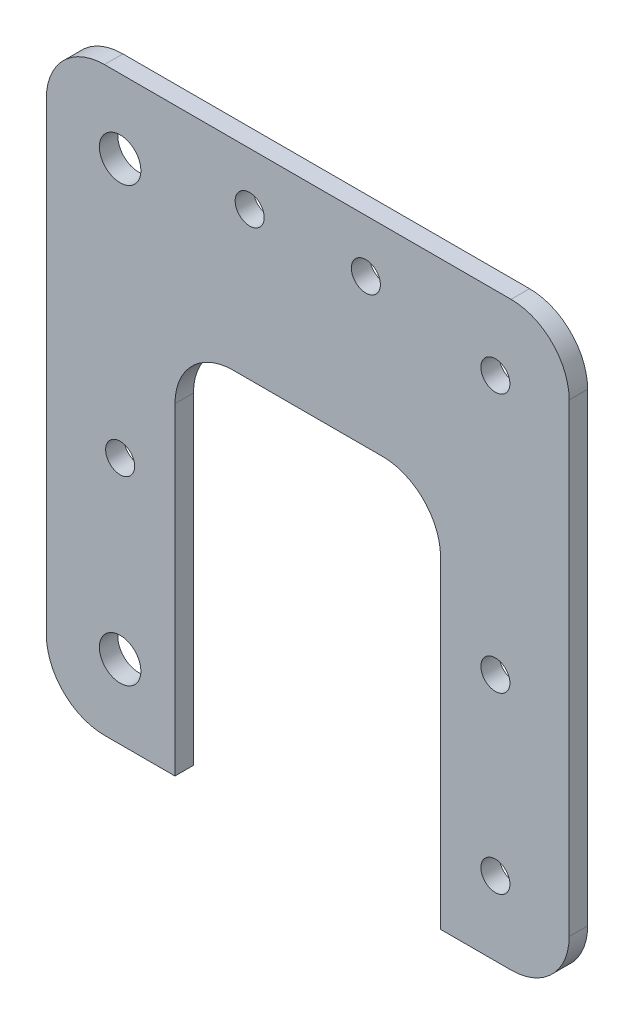
SolidWorks part; units mm, degrees
ref_plane "Front Plane" through (0, 0, 0) normal (0, 0, 1) x (1, 0, 0)
ref_plane "Top Plane" through (0, 0, 0) normal (0, 1, 0) x (1, 0, 0)
ref_plane "Right Plane" through (0, 0, 0) normal (1, 0, 0) x (0, 0, -1)
sketch "Sketch1" plane through (0, 0, 0) normal (0, 0, 1) x (1, 0, 0)
  line L1 (-45, -55) -> (45, -55)
  line L2 (-45, -55) -> (-45, 45)
  line L3 (-45, 45) -> (45, 45)
  line L4 (45, -55) -> (45, 45)
  line L8 (-32.3, 32.3) -> (-32.3, -42.3) construction
  line L9 (-32.3, -42.3) -> (32.3, -42.3) construction
  line L10 (32.3, -42.3) -> (32.3, 32.3) construction
  line L11 (32.3, 32.3) -> (-32.3, 32.3) construction
  line L12 (32.3, -12.3) -> (-32.3, -12.3) construction
  circle A4 centre (32.3, -12.3) radius 2.5
  circle A5 centre (32.3, -42.3) radius 2.5
  circle A6 centre (-32.3, -42.3) radius 3.57
  circle A7 centre (-32.3, -12.3) radius 2.5
  circle A9 centre (-32.3, 32.3) radius 3.57
  circle A11 centre (32.3, 32.3) radius 2.5
  dimension "D9" = 7.14
  dimension "D10" = 5
  dimension "D1" = 90
  dimension "D2" = 100
  dimension "D3" = 12.7
  dimension "D4" = 12.7
  dimension "D5" = 42.7
  dimension "D6" = 12.7
  dimension "D7" = 45
  dimension "D8" = 45
  dimension "D11" = 12.7
extrude "Boss-Extrude1" add sketch "Sketch1" against normal blind 3.18 from offset 19.16
sketch "Sketch2" plane through (0, 0, 15.98) normal (0, 0, -1) x (-1, 0, 0)
  line L0 (45, -55) -> (-45, -55) construction
  line L1 (-22.86, -55) -> (22.86, -55)
  line L2 (-22.86, -55) -> (-22.86, 10.5119)
  line L3 (-22.86, 10.5119) -> (22.86, 10.5119)
  line L4 (22.86, -55) -> (22.86, 10.5119)
  line L5 (0, 0) -> (0, 10.5119) construction
  dimension "D1" = 45.72
extrude "Cut-Extrude1" cut sketch "Sketch2" against normal through all
fillet "Fillet1" radius 10 6 edges at (45, -55, 17.57) (-45, -55, 17.57) (-45, 45, 17.57) (45, 45, 17.57) (-22.86, 10.5119, 17.57) (22.86, 10.5119, 17.57)
ref_plane "Midplane" through (0, -5, 0) normal (0, 1, 0) x (1, 0, 0)
sketch "Sketch3" plane through (0, 0, 19.16) normal (0, 0, 1) x (1, 0, 0)
  circle A0 centre (10, 35.9309) radius 2.5 construction
  circle A1 centre (-10, 35.9309) radius 2.5 construction
  circle A2 centre (10, 35.9309) radius 2.5
  circle A3 centre (-10, 35.9309) radius 2.5
extrude "Cut-Extrude2" cut sketch "Sketch3" against normal through all
